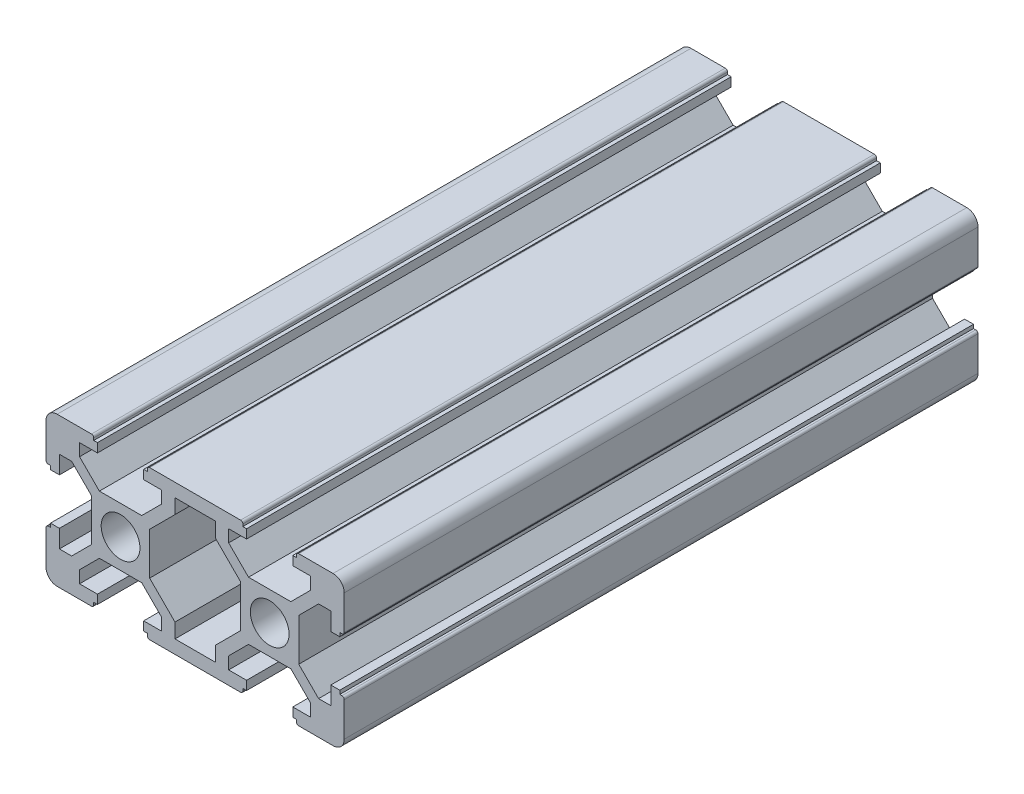
SolidWorks part; units mm, degrees
ref_plane "前视基准面" through (0, 0, 0) normal (0, 0, 1) x (1, 0, 0)
ref_plane "上视基准面" through (0, 0, 0) normal (0, 1, 0) x (1, 0, 0)
ref_plane "右视基准面" through (0, 0, 0) normal (1, 0, 0) x (0, 0, -1)
sketch "草图1" plane through (0, 0, 0) normal (0, 0, 1) x (1, 0, 0)
  line L0 (0, 0) -> (0, -41497.3383) construction
  line L1 (0, 0) -> (41497.3383, 0) construction
  line L2 (-13.9, 0) -> (-13.9, 2.8393)
  line L3 (-13.9, 2.8393) -> (-16.5607, 5.5)
  line L4 (-16.5607, 5.5) -> (-18.2, 5.5)
  line L5 (-18.2, 5.5) -> (-18.2, 3.1)
  line L6 (-18.2, 3.1) -> (-19.4, 3.1)
  line L7 (-19.4, 3.1) -> (-19.4, 3.6)
  line L8 (-19.4, 3.6) -> (-20, 3.6)
  line L9 (-20, 3.6) -> (-20, 10)
  line L10 (-20, 10) -> (-13.6, 10)
  line L11 (-13.6, 10) -> (-13.6, 9.4)
  line L12 (-13.6, 9.4) -> (-13.1, 9.4)
  line L13 (-13.1, 9.4) -> (-13.1, 8.2)
  line L14 (-13.1, 8.2) -> (-15.5, 8.2)
  line L15 (-15.5, 6.5607) -> (-12.8393, 3.9)
  line L16 (-12.8393, 3.9) -> (-7.1607, 3.9)
  line L17 (-4.5, 6.5607) -> (-7.1607, 3.9)
  line L18 (-4.5, 6.5607) -> (-4.5, 8.2)
  line L19 (-4.5, 8.2) -> (-6.9, 8.2)
  line L20 (-6.9, 8.2) -> (-6.9, 9.4)
  line L21 (-6.9, 9.4) -> (-6.4, 9.4)
  line L22 (-6.4, 9.4) -> (-6.4, 10)
  line L23 (-6.4, 10) -> (6.4, 10)
  line L24 (-15.5, 8.2) -> (-15.5, 6.5607)
  line L25 (-10, 0) -> (-20, 10) construction
  line L26 (-6.1, -2.8393) -> (-6.1, 2.8393)
  line L27 (-6.1, 2.8393) -> (-2.7, 6.2393)
  line L28 (-2.7, 6.2393) -> (-2.7, 8.2)
  line L29 (-2.7, 8.2) -> (2.7, 8.2)
  line L30 (-10, 0) -> (0, 10) construction
  line L31 (13.9, 0) -> (13.9, 2.8393)
  line L32 (6.1, -2.8393) -> (6.1, 2.8393)
  line L33 (4.5, 6.5607) -> (7.1607, 3.9)
  line L34 (12.8393, 3.9) -> (7.1607, 3.9)
  line L35 (6.1, 2.8393) -> (2.7, 6.2393)
  line L36 (2.7, 6.2393) -> (2.7, 8.2)
  line L37 (4.5, 6.5607) -> (4.5, 8.2)
  line L38 (6.4, 9.4) -> (6.4, 10)
  line L39 (6.9, 9.4) -> (6.4, 9.4)
  line L40 (6.9, 8.2) -> (6.9, 9.4)
  line L41 (4.5, 8.2) -> (6.9, 8.2)
  line L42 (13.1, 9.4) -> (13.1, 8.2)
  line L43 (13.6, 9.4) -> (13.1, 9.4)
  line L44 (13.6, 10) -> (13.6, 9.4)
  line L45 (20, 10) -> (13.6, 10)
  line L46 (20, 3.6) -> (20, 10)
  line L47 (19.4, 3.6) -> (20, 3.6)
  line L48 (19.4, 3.1) -> (19.4, 3.6)
  line L49 (18.2, 3.1) -> (19.4, 3.1)
  line L50 (18.2, 5.5) -> (18.2, 3.1)
  line L51 (16.5607, 5.5) -> (18.2, 5.5)
  line L52 (13.9, 2.8393) -> (16.5607, 5.5)
  line L53 (15.5, 6.5607) -> (12.8393, 3.9)
  line L54 (15.5, 8.2) -> (15.5, 6.5607)
  line L55 (13.1, 8.2) -> (15.5, 8.2)
  line L56 (15.5, -6.5607) -> (12.8393, -3.9)
  line L57 (13.9, -2.8393) -> (16.5607, -5.5)
  line L58 (16.5607, -5.5) -> (18.2, -5.5)
  line L59 (18.2, -5.5) -> (18.2, -3.1)
  line L60 (18.2, -3.1) -> (19.4, -3.1)
  line L61 (19.4, -3.1) -> (19.4, -3.6)
  line L62 (19.4, -3.6) -> (20, -3.6)
  line L63 (12.8393, -3.9) -> (7.1607, -3.9)
  line L64 (13.9, 0) -> (13.9, -2.8393)
  line L65 (13.1, -8.2) -> (15.5, -8.2)
  line L66 (15.5, -8.2) -> (15.5, -6.5607)
  line L67 (20, -3.6) -> (20, -10)
  line L68 (20, -10) -> (13.6, -10)
  line L69 (13.6, -10) -> (13.6, -9.4)
  line L70 (13.6, -9.4) -> (13.1, -9.4)
  line L71 (13.1, -9.4) -> (13.1, -8.2)
  line L72 (4.5, -8.2) -> (6.9, -8.2)
  line L73 (6.9, -8.2) -> (6.9, -9.4)
  line L74 (6.9, -9.4) -> (6.4, -9.4)
  line L75 (6.4, -9.4) -> (6.4, -10)
  line L76 (4.5, -6.5607) -> (4.5, -8.2)
  line L77 (2.7, -6.2393) -> (2.7, -8.2)
  line L78 (6.1, -2.8393) -> (2.7, -6.2393)
  line L79 (4.5, -6.5607) -> (7.1607, -3.9)
  line L80 (-2.7, -8.2) -> (2.7, -8.2)
  line L81 (-2.7, -6.2393) -> (-2.7, -8.2)
  line L82 (-6.1, -2.8393) -> (-2.7, -6.2393)
  line L83 (-4.5, -6.5607) -> (-7.1607, -3.9)
  line L84 (-4.5, -8.2) -> (-6.9, -8.2)
  line L85 (-4.5, -6.5607) -> (-4.5, -8.2)
  line L86 (-6.4, -10) -> (6.4, -10)
  line L87 (-6.4, -9.4) -> (-6.4, -10)
  line L88 (-6.9, -9.4) -> (-6.4, -9.4)
  line L89 (-6.9, -8.2) -> (-6.9, -9.4)
  line L90 (-13.1, -9.4) -> (-13.1, -8.2)
  line L91 (-13.6, -9.4) -> (-13.1, -9.4)
  line L92 (-13.6, -10) -> (-13.6, -9.4)
  line L93 (-15.5, -8.2) -> (-15.5, -6.5607)
  line L94 (-13.1, -8.2) -> (-15.5, -8.2)
  line L95 (-12.8393, -3.9) -> (-7.1607, -3.9)
  line L96 (-15.5, -6.5607) -> (-12.8393, -3.9)
  line L97 (-13.9, 0) -> (-13.9, -2.8393)
  line L98 (-13.9, -2.8393) -> (-16.5607, -5.5)
  line L99 (-19.4, -3.6) -> (-20, -3.6)
  line L100 (-19.4, -3.1) -> (-19.4, -3.6)
  line L101 (-18.2, -3.1) -> (-19.4, -3.1)
  line L102 (-18.2, -5.5) -> (-18.2, -3.1)
  line L103 (-16.5607, -5.5) -> (-18.2, -5.5)
  line L104 (-20, -3.6) -> (-20, -10)
  line L105 (-20, -10) -> (-13.6, -10)
  circle A0 centre (-10, 0) radius 2.6
  circle A1 centre (10, 0) radius 2.6
  point P50 (0, 8.2)
  point P95 (6.1, 0)
  point P96 (-6.1, 0)
  dimension "D1" = 5.2
  dimension "D2" = 45
  dimension "D3" = 1.5
  dimension "D4" = 20
  dimension "D5" = 40
  dimension "D6" = 0.75
  dimension "D7" = 7.2
  dimension "D8" = 6.2
  dimension "D9" = 6.1
  dimension "D10" = 1.8
  dimension "D11" = 1.2
  dimension "D12" = 12.2
  dimension "D13" = 5.4
  dimension "D14" = 11
  dimension "D15" = 1.5
  dimension "D16" = 0.75
extrude "凸台-拉伸1" add sketch "草图1" along normal mid plane 85
fillet "圆角1" radius 1.5 4 edges at (20, -10, 0) (20, 10, 0) (-20, -10, 0) (-20, 10, 0)
fillet "圆角2" radius 0.3 12 edges at (-6.4, 10, 0) (-13.6, 10, 0) (-20, 3.6, 0) (-20, -3.6, 0) (-13.6, -10, 0) (-6.4, -10, 0) (6.4, -10, 0) (20, -3.6, 0) (20, 3.6, 0) (13.6, -10, 0) (13.6, 10, 0) (6.4, 10, 0)
equation "\"D6@草图1\"=1/2*\"D3@草图1\""
equation "\"D16@草图1\"=0.5*\"D15@草图1\""
